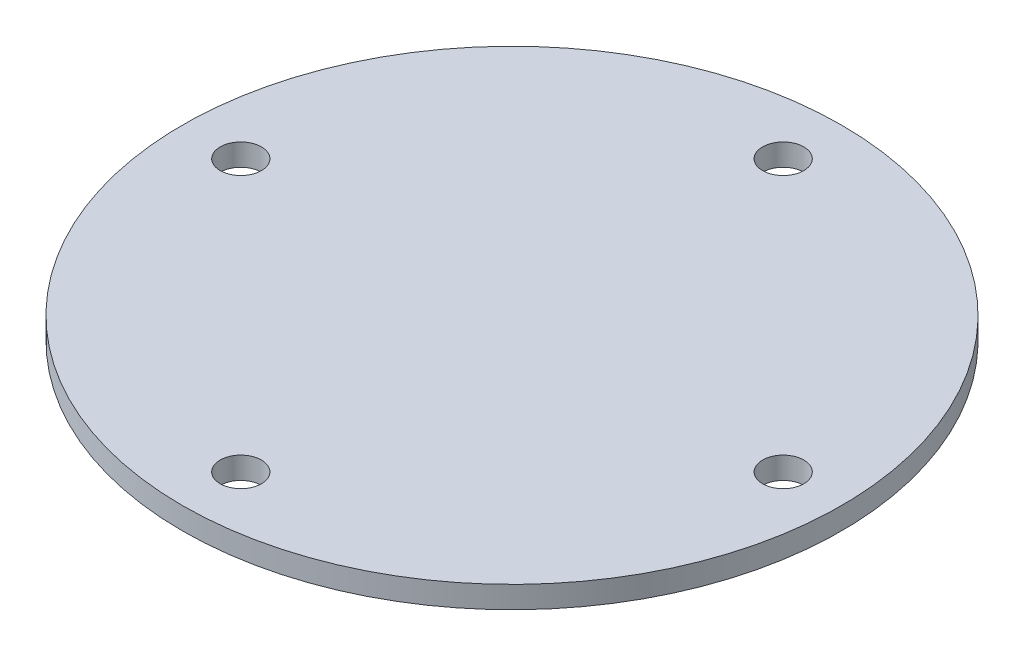
SolidWorks part; units mm, degrees
ref_plane "Front Plane" through (0, 0, 0) normal (0, 0, 1) x (1, 0, 0)
ref_plane "Top Plane" through (0, 0, 0) normal (0, 1, 0) x (1, 0, 0)
ref_plane "Right Plane" through (0, 0, 0) normal (1, 0, 0) x (0, 0, -1)
sketch "Sketch1" plane through (0, 0, 0) normal (0, 1, 0) x (1, 0, 0)
  circle A0 centre (0, 0) radius 24
  circle A1 centre (0, 19.75) radius 1.5
  circle A2 centre (0, 0) radius 24
  circle A3 centre (19.75, 0) radius 1.5
  circle A4 centre (0, 0) radius 24
  circle A5 centre (0, -19.75) radius 1.5
  circle A6 centre (0, 0) radius 24
  circle A7 centre (-19.75, 0) radius 1.5
  point P5 (0, 0)
  point P6 (0, 0)
  point P17 (0, 0)
  dimension "D2" = 48
  dimension "D3" = 39.5
  dimension "D4" = 3
  dimension "D1" = 4
extrude "Boss-Extrude1" add sketch "Sketch1" along normal mid plane 1.6 contours A0 A7 A5 A3 A1
